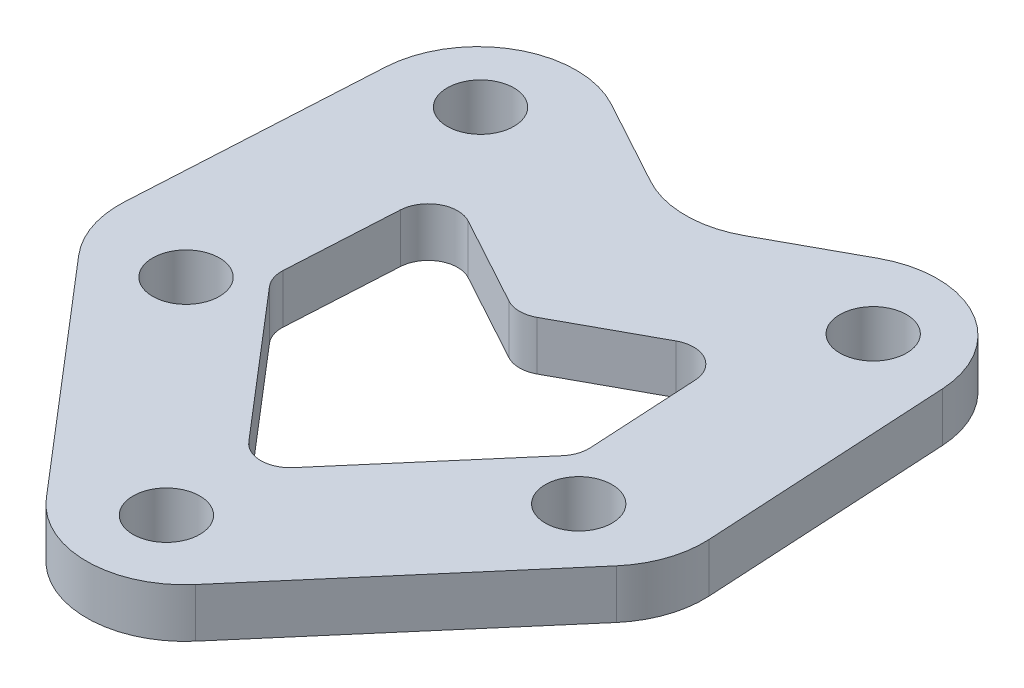
SolidWorks part; units mm, degrees
ref_plane "Front Plane" through (0, 0, 0) normal (0, 0, 1) x (1, 0, 0)
ref_plane "Top Plane" through (0, 0, 0) normal (0, 1, 0) x (1, 0, 0)
ref_plane "Right Plane" through (0, 0, 0) normal (1, 0, 0) x (0, 0, -1)
sketch "Sketch1" plane through (0, 0, 0) normal (0, 1, 0) x (1, 0, 0)
  line L0 (-17.4625, 31.75) -> (0, 22.225)
  line L1 (0, 22.225) -> (17.4625, 31.75)
  line L2 (17.4625, 31.75) -> (19.05, 3.175)
  line L3 (19.05, 3.175) -> (0, -19.05)
  line L4 (0, -19.05) -> (-19.05, 3.175)
  line L5 (-19.05, 3.175) -> (-17.4625, 31.75)
  dimension "D1" = 34.925
  dimension "D2" = 22.225
  dimension "D3" = 19.05
  dimension "D4" = 19.05
  dimension "D5" = 3.175
  dimension "D6" = 9.525
extrude "Boss-Extrude1" add sketch "Sketch1" along normal blind 3.175
sketch "Sketch2" plane through (0, 3.175, 0) normal (0, 1, 0) x (1, 0, 0)
  circle A0 centre (0, -10.4775) radius 2.159
  circle A1 centre (-12.7, 3.4925) radius 2.159
  circle A2 centre (12.7, 3.4925) radius 2.159
  circle A3 centre (-12.7, 22.5425) radius 2.159
  circle A4 centre (12.7, 22.5425) radius 2.159
  circle A5 centre (-12.7, 3.4925) radius 7.239 construction
  dimension "D1" = 4.318
  dimension "D3" = 25.4
  dimension "D2" = 10.4775
  dimension "D4" = 19.05
extrude "Cut-Extrude1" cut sketch "Sketch2" against normal through all
sketch "Sketch3" plane through (0, 3.175, 0) normal (0, 1, 0) x (1, 0, 0)
  line L27 (-9.3667, 17.2076) -> (-9.9755, 6.2484)
  line L28 (-9.9755, 6.2484) -> (0, -5.3897)
  line L29 (0, -5.3897) -> (9.9755, 6.2484)
  line L30 (9.9755, 6.2484) -> (9.3667, 17.2076)
  line L31 (9.3667, 17.2076) -> (0, 12.0985)
  line L32 (0, 12.0985) -> (-9.3667, 17.2076)
  line L33 (-9.3667, 17.2076) -> (-9.9755, 6.2484)
  line L34 (-9.9755, 6.2484) -> (0, -5.3897)
  line L35 (0, -5.3897) -> (9.9755, 6.2484)
  line L36 (9.9755, 6.2484) -> (9.3667, 17.2076)
  line L37 (9.3667, 17.2076) -> (0, 12.0985)
  line L38 (0, 12.0985) -> (-9.3667, 17.2076)
  dimension "D1" = 8.89
extrude "Cut-Extrude2" cut sketch "Sketch3" against normal through all
fillet "Fillet1" radius 6.35 6 edges at (-19.05, 1.5875, -3.175) (0, 1.5875, 19.05) (19.05, 1.5875, -3.175) (17.4625, 1.5875, -31.75) (-17.4625, 1.5875, -31.75) (0, 1.5875, -22.225)
fillet "Fillet2" radius 1.905 6 edges at (-9.9755, 1.5875, -6.2484) (-9.3667, 1.5875, -17.2076) (0, 1.5875, -12.0985) (9.3667, 1.5875, -17.2076) (9.9755, 1.5875, -6.2484) (0, 1.5875, 5.3897)
